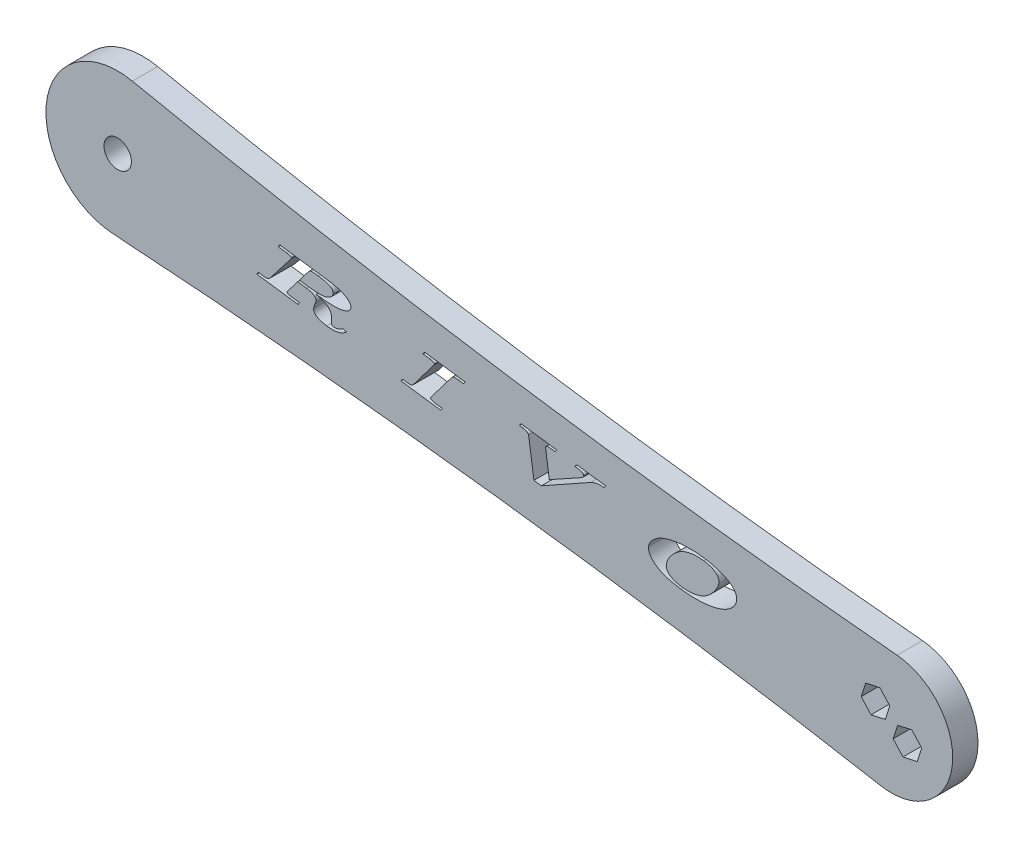
SolidWorks part; units mm, degrees
ref_plane "Front Plane" through (0, 0, 0) normal (0, 0, 1) x (1, 0, 0)
ref_plane "Top Plane" through (0, 0, 0) normal (0, 1, 0) x (1, 0, 0)
ref_plane "Right Plane" through (0, 0, 0) normal (1, 0, 0) x (0, 0, -1)
sketch "Sketch1" plane through (0, 0, 0) normal (0, 0, 1) x (1, 0, 0)
  circle A0 centre (0, 0) radius 75
  dimension "D1" = 150
extrude "Boss-Extrude1" add sketch "Sketch1" along normal blind 6
sketch "Sketch2" plane through (0, 0, 0) normal (0, 0, -1) x (-1, 0, 0)
  arc A4 (128.7472, -9.4164) -> (-53.0741, -31.7133) centre (232.6338, -1609.0465) ccw
  arc A5 (-56.9882, -3.0066) -> (-53.0741, -31.7133) centre (-55.6585, -17.4455) ccw
  arc A6 (-56.9882, -3.0066) -> (124.1653, 24.1878) centre (-203.9957, 1593.2383) ccw
  arc A7 (128.7472, -9.4164) -> (124.1653, 24.1878) centre (127.6455, 7.5479) ccw
  arc A8 (128.7472, -9.4164) -> (-53.0741, -31.7133) centre (232.6338, -1609.0465) ccw
  arc A9 (-56.9882, -3.0066) -> (-53.0741, -31.7133) centre (-55.6585, -17.4455) ccw
  arc A10 (-56.9882, -3.0066) -> (124.1653, 24.1878) centre (-203.9957, 1593.2383) ccw
  arc A11 (128.7472, -9.4164) -> (124.1653, 24.1878) centre (127.6455, 7.5479) ccw
  dimension "D1" = 0
extrude "Boss-Extrude2" add sketch "Sketch2" along normal blind 6
sketch "Sketch3" plane through (0, 0, 6) normal (0, 0, 1) x (1, 0, 0)
  circle A0 centre (0, 0) radius 92.1344
extrude "Cut-Extrude1" cut sketch "Sketch3" against normal up to surface (6 mm away) up to face at (-104.902, 4.4449, 0)
sketch "Sketch4" plane through (0, 0, 0) normal (0, 0, 1) x (1, 0, 0)
  line L0 (-144.608, 6.42) -> (68.6704, -23.8439) construction
  arc A2 (53.0741, -31.7133) -> (56.9882, -3.0066) centre (55.6585, -17.4455) ccw construction
  arc A3 (-124.1653, 24.1878) -> (-128.7472, -9.4164) centre (-127.6455, 7.5479) ccw construction
  text T0 "RIVO" font "Century Schoolbook" height in points 36
  point P2 (-142.878, 0)
  point P5 (67.2976, -26.093)
  point P10 (68.32, -24.5119)
  point P12 (-144.183, 3.6097)
  point P13 (68.6704, -23.8439)
  point P14 (-144.608, 6.42)
extrude "Cut-Extrude2" cut sketch "Sketch4" against normal blind 6
sketch "Sketch5" plane through (0, 0, 0) normal (0, 0, 1) x (1, 0, 0)
  line L6 (55.2598, -14.276) -> (52.9313, -11.7112)
  line L7 (54.2029, -17.5749) -> (55.2598, -14.276)
  line L8 (50.8175, -18.3091) -> (54.2029, -17.5749)
  line L9 (48.489, -15.7443) -> (50.8175, -18.3091)
  line L10 (49.5459, -12.4454) -> (48.489, -15.7443)
  line L11 (52.9313, -11.7112) -> (49.5459, -12.4454)
  line L12 (55.2598, -14.276) -> (52.9313, -11.7112)
  line L13 (54.2029, -17.5749) -> (55.2598, -14.276)
  line L14 (50.8175, -18.3091) -> (54.2029, -17.5749)
  line L15 (48.489, -15.7443) -> (50.8175, -18.3091)
  line L16 (49.5459, -12.4454) -> (48.489, -15.7443)
  line L17 (52.9313, -11.7112) -> (49.5459, -12.4454)
  line L18 (56.0571, -20.615) -> (58.3856, -23.1798)
  line L19 (57.114, -17.3161) -> (56.0571, -20.615)
  line L20 (60.4994, -16.5819) -> (57.114, -17.3161)
  line L21 (62.8279, -19.1467) -> (60.4994, -16.5819)
  line L22 (61.771, -22.4456) -> (62.8279, -19.1467)
  line L23 (58.3856, -23.1798) -> (61.771, -22.4456)
  line L24 (56.0571, -20.615) -> (58.3856, -23.1798)
  line L25 (57.114, -17.3161) -> (56.0571, -20.615)
  line L26 (60.4994, -16.5819) -> (57.114, -17.3161)
  line L27 (62.8279, -19.1467) -> (60.4994, -16.5819)
  line L28 (61.771, -22.4456) -> (62.8279, -19.1467)
  line L29 (58.3856, -23.1798) -> (61.771, -22.4456)
  circle A1 centre (-127.6455, 7.5479) radius 3.25
  circle A2 centre (-127.6455, 7.5479) radius 3.25
  dimension "D1" = 0
  dimension "D2" = 0
  dimension "D3" = 0
extrude "Cut-Extrude3" cut sketch "Sketch5" against normal through all
